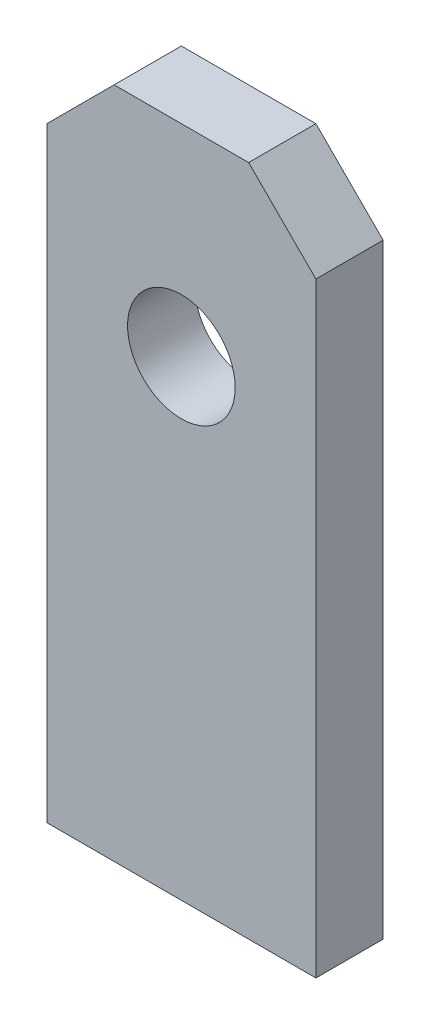
SolidWorks part; units mm, degrees
ref_plane "Front Plane" through (0, 0, 0) normal (0, 0, 1) x (1, 0, 0)
ref_plane "Top Plane" through (0, 0, 0) normal (0, 1, 0) x (1, 0, 0)
ref_plane "Right Plane" through (0, 0, 0) normal (1, 0, 0) x (0, 0, -1)
sketch "Sketch1" plane through (0, 0, 0) normal (0, 0, 1) x (1, 0, 0)
  line L6 (20, 0) -> (-20, 0)
  line L7 (20, 0) -> (20, 90)
  line L8 (-10, 100) -> (10, 100)
  line L9 (20, 90) -> (10, 100)
  line L11 (-20, 0) -> (-20, 90)
  line L12 (-20, 90) -> (-10, 100)
  circle A0 centre (0, 70) radius 8
  dimension "D6" = 16
  dimension "D1" = 40
  dimension "D2" = 20
  dimension "D3" = 90
  dimension "D4" = 20
  dimension "D5" = 100
  dimension "D7" = 70
extrude "Boss-Extrude1" add sketch "Sketch1" along normal blind 10 contours L7 L9 L8 L12 L11 L6
sketch "Sketch2" plane through (0, 0, 10) normal (0, 0, 1) x (1, 0, 0)
  line L0 (20, 0) -> (-20, 0) construction
  circle A0 centre (0, 70) radius 8
  dimension "D1" = 16
  dimension "D2" = 70
extrude "Cut-Extrude1" cut sketch "Sketch2" against normal blind 10
